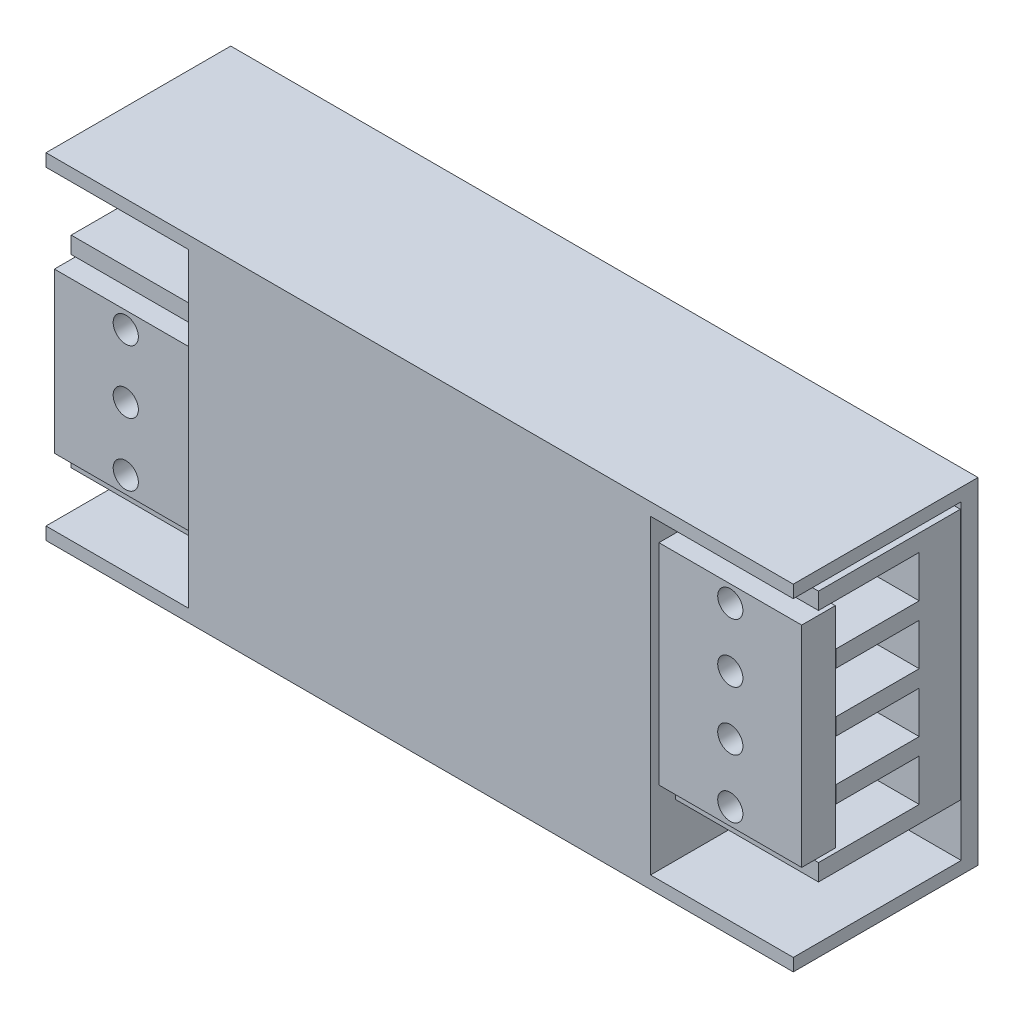
SolidWorks part; units mm, degrees
ref_plane "Front Plane" through (0, 0, 0) normal (0, 0, 1) x (1, 0, 0)
ref_plane "Top Plane" through (0, 0, 0) normal (0, 1, 0) x (1, 0, 0)
ref_plane "Right Plane" through (0, 0, 0) normal (1, 0, 0) x (0, 0, -1)
sketch "Sketch1" plane through (0, 0, 0) normal (0, 0, 1) x (1, 0, 0)
  line L1 (-44.5, 20) -> (44.5, 20)
  line L2 (-44.5, 20) -> (-44.5, -20)
  line L3 (-44.5, -20) -> (44.5, -20)
  line L4 (44.5, 20) -> (44.5, -20)
  line L5 (-44.5, 20) -> (44.5, -20) construction
  line L6 (-44.5, -20) -> (44.5, 20) construction
  point P0 (0, 0)
  dimension "D1" = 89
  dimension "D2" = 40
extrude "Boss-Extrude1" add sketch "Sketch1" along normal blind 22
sketch "Sketch2" plane through (0, 0, 22) normal (0, 0, 1) x (1, 0, 0)
  line L0 (44.5, 18.5) -> (-44.5, 18.5)
  line L1 (-44.5, -18.5) -> (44.5, -18.5)
  line L2 (-27.5, 18.5) -> (-27.5, -18.5)
  line L3 (27.5, 18.5) -> (27.5, -18.5)
  line L4 (44.5, -20) -> (44.5, 20)
  line L5 (44.5, 20) -> (-44.5, 20)
  line L6 (-44.5, 20) -> (-44.5, -20)
  line L7 (-44.5, -20) -> (44.5, -20)
  line L8 (44.5, -20) -> (44.5, 20)
  line L9 (44.5, 20) -> (-44.5, 20)
  line L10 (-44.5, 20) -> (-44.5, -20)
  line L11 (-44.5, -20) -> (44.5, -20)
  line M7 (44.5, -20) -> (44.5, 20)
  line M9 (-44.5, 20) -> (-44.5, -20)
  dimension "D3" = 17
  dimension "D4" = 17
  dimension "D1" = 0
  dimension "D2" = 1.5
extrude "Cut-Extrude1" cut sketch "Sketch2" against normal blind 20 contours L2 L0 L1 M9 | L0 L3 L1 M7
sketch "Sketch3" plane through (0, 0, 2) normal (0, 0, 1) x (1, 0, 0)
  line L0 (-44.5, 18.5) -> (-44.5, -18.5) construction
  line L1 (-44.5, 8) -> (-27.5, 8)
  line L2 (-44.5, 8) -> (-44.5, -12)
  line L3 (-44.5, -12) -> (-27.5, -12)
  line L4 (-27.5, 8) -> (-27.5, -12)
  line L5 (-27.5, 18.5) -> (-27.5, -18.5) construction
  line L6 (44.5, 20) -> (-44.5, 20) construction
  line L8 (-27.5, 1) -> (-44.5, 1)
  line L9 (-27.5, 1) -> (-27.5, 3)
  line L10 (-27.5, 3) -> (-44.5, 3)
  line L11 (-44.5, 1) -> (-44.5, 3)
  line L12 (-44.5, -5) -> (-27.5, -5)
  line L13 (-44.5, -5) -> (-44.5, -7)
  line L14 (-44.5, -7) -> (-27.5, -7)
  line L15 (-27.5, -5) -> (-27.5, -7)
  line L16 (-44.5, 8) -> (-27.5, 8)
  line L17 (-44.5, 8) -> (-44.5, 10)
  line L18 (-44.5, 10) -> (-27.5, 10)
  line L19 (-27.5, 8) -> (-27.5, 10)
  line L20 (-44.5, -12) -> (-27.5, -12)
  line L21 (-44.5, -12) -> (-44.5, -14)
  line L22 (-44.5, -14) -> (-27.5, -14)
  line L23 (-27.5, -12) -> (-27.5, -14)
  line M7 (-27.5, -18.5) -> (-27.5, 18.5)
  line M9 (-44.5, 18.5) -> (-44.5, -18.5)
  dimension "D1" = 20
  dimension "D2" = 12
  dimension "D3" = 2
  dimension "D4" = 2
  dimension "D5" = 5
  dimension "D6" = 5
  dimension "D7" = 2
  dimension "D8" = 2
extrude "Boss-Extrude2" add sketch "Sketch3" along normal blind 17 contours L18 L1 M9 M7 | L4 L10 L2 L8 | L14 L4 L12 M9 | L22 L3 M9 M7
sketch "Sketch4" plane through (0, 0, 19) normal (0, 0, 1) x (1, 0, 0)
  line L4 (-44.5, 7.5) -> (-44.5, -11.5)
  line L7 (-44.5, 8) -> (-27.5, 8) construction
  line L8 (-44.5, -7) -> (-27.5, -7) construction
  line L15 (-44.5, 10) -> (-44.5, 8) construction
  line L17 (-44.5, 10) -> (-27.5, 10) construction
  line L19 (-27.5, 7.5) -> (-27.5, -11.5)
  line L21 (-44.5, -11.5) -> (-27.5, -11.5)
  line L22 (-44.5, 7.5) -> (-27.5, 7.5)
  line L23 (44.5, 20) -> (-44.5, 20) construction
  circle A0 centre (-36, 5.5) radius 1.5
  circle A1 centre (-36, -2) radius 1.5
  circle A2 centre (-36, -9.5) radius 1.5
  dimension "D1" = 2.5
  dimension "D2" = 3
  dimension "D4" = 12
  dimension "D6" = 17
  dimension "D3" = 8.5
  dimension "D5" = 19
  dimension "D7" = 2.5
  dimension "D8" = 12.5
extrude "Boss-Extrude10" add sketch "Sketch4" against normal blind 2 and the other way blind 2
sketch "Sketch5" plane through (0, 0, 2) normal (0, 0, 1) x (1, 0, 0)
  line L0 (27.5, 18.5) -> (27.5, -18.5) construction
  line L1 (27.5, 17.778) -> (44.5, 17.778)
  line L2 (27.5, 17.778) -> (27.5, -12.222)
  line L3 (27.5, -12.222) -> (44.5, -12.222)
  line L4 (44.5, 17.778) -> (44.5, -12.222)
  line L5 (44.5, -18.5) -> (44.5, 18.5) construction
  line L6 (27.5, 15.778) -> (44.5, 15.778)
  line L7 (27.5, 10.778) -> (44.5, 10.778)
  line L8 (27.5, 10.778) -> (27.5, 8.778)
  line L9 (27.5, 8.778) -> (44.5, 8.778)
  line L10 (44.5, 10.778) -> (44.5, 8.778)
  line L11 (27.5, -10.222) -> (44.5, -10.222)
  line L12 (27.5, 3.778) -> (44.5, 3.778)
  line L13 (27.5, 3.778) -> (27.5, 1.778)
  line L14 (27.5, 1.778) -> (44.5, 1.778)
  line L15 (44.5, 3.778) -> (44.5, 1.778)
  line L16 (27.5, -3.222) -> (44.5, -3.222)
  line L17 (27.5, -3.222) -> (27.5, -5.222)
  line L18 (27.5, -5.222) -> (44.5, -5.222)
  line L19 (44.5, -3.222) -> (44.5, -5.222)
  line L21 (44.5, 18.5) -> (27.5, 18.5) construction
  line M14 (27.5, 18.5) -> (27.5, -18.5)
  line M16 (44.5, -18.5) -> (44.5, 18.5)
  dimension "D1" = 30
  dimension "D2" = 0.722
  dimension "D3" = 2.722
  dimension "D4" = 7.722
  dimension "D5" = 9.722
  dimension "D6" = 14.722
  dimension "D7" = 21.722
  dimension "D10" = 28.722
extrude "Boss-Extrude11" add sketch "Sketch5" along normal blind 17 contours L6 L4 L1 M14 | L9 L4 L7 M14 | L14 L12 M14 M16 | L18 L16 M14 M16 | L11 L3 M14 M16
sketch "Sketch6" plane through (0, 0, 19) normal (0, 0, 1) x (1, 0, 0)
  line L0 (27.5, 18.5) -> (27.5, -18.5) construction
  line L1 (27.5, 15.778) -> (44.5, 15.778) construction
  line L3 (27.5, 15.278) -> (27.5, -9.722)
  line L6 (44.5, 15.278) -> (44.5, -9.722)
  line L8 (27.5, -5.222) -> (44.5, -5.222) construction
  line L9 (27.5, 1.778) -> (44.5, 1.778) construction
  line L10 (27.5, 8.778) -> (44.5, 8.778) construction
  line L11 (27.5, 15.278) -> (44.5, 15.278)
  line L12 (44.5, -9.722) -> (27.5, -9.722)
  line L13 (-44.5, -20) -> (44.5, -20) construction
  circle A0 centre (36, 13.278) radius 1.5
  circle A1 centre (36, 6.278) radius 1.5
  circle A2 centre (36, -0.722) radius 1.5
  circle A3 centre (36, -7.722) radius 1.5
  point P18 (36, 1.778)
  dimension "D1" = 3
  dimension "D2" = 2.5
  dimension "D3" = 2.5
  dimension "D4" = 2.5
  dimension "D5" = 25
  dimension "D6" = 8.5
  dimension "D7" = 8.5
  dimension "D8" = 8.5
  dimension "D9" = 8.5
  dimension "D10" = 0.5
  dimension "D12" = 2
  dimension "D13" = 10.278
extrude "Boss-Extrude13" add sketch "Sketch6" against normal blind 2 and the other way blind 2
sketch "Sketch7" plane through (-44.5, 0, 0) normal (-1, 0, 0) x (0, 0, 1)
  line L0 (19, 8) -> (2, 8) construction
  line L1 (2, 10) -> (2.1, 10)
  line L2 (2, 10) -> (2, 8)
  line L3 (2, 8) -> (2.1, 8)
  line L4 (2.1, 10) -> (2.1, 8)
  line L5 (17, 1) -> (2, 1) construction
  line L6 (2, 3) -> (2.1, 3)
  line L7 (2, 3) -> (2, 1)
  line L8 (2, 1) -> (2.1, 1)
  line L9 (2.1, 3) -> (2.1, 1)
  line L10 (17, -7) -> (2, -7) construction
  line L11 (2, -5) -> (2.1, -5)
  line L12 (2, -5) -> (2, -7)
  line L13 (2, -7) -> (2.1, -7)
  line L14 (2.1, -5) -> (2.1, -7)
  line L15 (19, -14) -> (2, -14) construction
  line L16 (2, -12) -> (2.1, -12)
  line L17 (2, -12) -> (2, -14)
  line L18 (2, -14) -> (2.1, -14)
  line L19 (2.1, -12) -> (2.1, -14)
  line L21 (17, -5) -> (16.9, -5)
  line L22 (17, -5) -> (17, -7)
  line L23 (17, -7) -> (16.9, -7)
  line L24 (16.9, -5) -> (16.9, -7)
  line L25 (17, 3) -> (16.9, 3)
  line L26 (17, 3) -> (17, 1)
  line L27 (17, 1) -> (16.9, 1)
  line L28 (16.9, 3) -> (16.9, 1)
  point P21 (2, -6)
  dimension "D1" = 0.1
  dimension "D2" = 0.1
  dimension "D3" = 0.1
  dimension "D4" = 0.1
  dimension "D5" = 0.1
  dimension "D6" = 0.1
extrude "Cut-Extrude2" cut sketch "Sketch7" against normal up to surface (17 mm away) up to face at (-27.5, -2, 9.5)
sketch "Sketch8" plane through (44.5, 0, 0) normal (1, 0, 0) x (0, 0, -1)
  line L5 (-17, -3.222) -> (-2, -3.222) construction
  line L6 (-2, -5.222) -> (-2.1, -5.222)
  line L7 (-2, -5.222) -> (-2, -3.222)
  line L8 (-2, -3.222) -> (-2.1, -3.222)
  line L9 (-2.1, -5.222) -> (-2.1, -3.222)
  line L10 (-17, -5.222) -> (-2, -5.222) construction
  line L11 (-17, -3.222) -> (-16.9, -3.222)
  line L12 (-17, -3.222) -> (-17, -5.222)
  line L13 (-17, -5.222) -> (-16.9, -5.222)
  line L14 (-16.9, -3.222) -> (-16.9, -5.222)
  line L15 (-17, 1.778) -> (-2, 1.778) construction
  line L16 (-17, 3.778) -> (-16.9, 3.778)
  line L17 (-17, 3.778) -> (-17, 1.778)
  line L18 (-17, 1.778) -> (-16.9, 1.778)
  line L19 (-16.9, 3.778) -> (-16.9, 1.778)
  line L20 (-17, 8.778) -> (-2, 8.778) construction
  line L21 (-17, 10.778) -> (-16.9, 10.778)
  line L22 (-17, 10.778) -> (-17, 8.778)
  line L23 (-17, 8.778) -> (-16.9, 8.778)
  line L24 (-16.9, 10.778) -> (-16.9, 8.778)
  line L25 (-19, 17.778) -> (-2, 17.778) construction
  line L30 (-17, 3.778) -> (-2, 3.778) construction
  line L31 (-2, 15.778) -> (-2.1, 15.778)
  line L32 (-2, 15.778) -> (-2, 17.778)
  line L33 (-2, 17.778) -> (-2.1, 17.778)
  line L34 (-2.1, 15.778) -> (-2.1, 17.778)
  line L35 (-2, 10.778) -> (-2.1, 10.778)
  line L36 (-2, 10.778) -> (-2, 8.778)
  line L37 (-2, 8.778) -> (-2.1, 8.778)
  line L38 (-2.1, 10.778) -> (-2.1, 8.778)
  line L39 (-2, 1.778) -> (-2.1, 1.778)
  line L40 (-2, 1.778) -> (-2, 3.778)
  line L41 (-2, 3.778) -> (-2.1, 3.778)
  line L42 (-2.1, 1.778) -> (-2.1, 3.778)
  line L43 (-19, -12.222) -> (-2, -12.222) construction
  line L48 (-2, -10.222) -> (-2.1, -10.222)
  line L49 (-2, -10.222) -> (-2, -12.222)
  line L50 (-2, -12.222) -> (-2.1, -12.222)
  line L51 (-2.1, -10.222) -> (-2.1, -12.222)
  point P59 (-17, 2.778)
  point P60 (-17, -4.222)
  dimension "D1" = 0.1
  dimension "D2" = 0.1
  dimension "D3" = 0.1
  dimension "D4" = 0.1
  dimension "D5" = 0.1
  dimension "D6" = 0.1
  dimension "D7" = 0.1
  dimension "D8" = 0.1
extrude "Cut-Extrude11" cut sketch "Sketch8" against normal up to surface (17 mm away) up to face at (27.5, -0.722, 9.5)
sketch "Sketch10" plane through (0, 0, 2) normal (0, 0, 1) x (1, 0, 0)
  line L0 (-27.5, 8) -> (-44.5, 8) construction
  line L1 (-27.5, 8) -> (-44.5, 8)
  line L2 (-27.5, 3) -> (-44.5, 3) construction
  line L3 (-27.5, 3) -> (-44.5, 3)
  line L4 (-27.5, 1) -> (-44.5, 1) construction
  line L5 (-27.5, 1) -> (-44.5, 1)
  line L6 (-27.5, -5) -> (-44.5, -5) construction
  line L7 (-27.5, -5) -> (-44.5, -5)
  line L8 (-27.5, -7) -> (-44.5, -7) construction
  line L9 (-27.5, -7) -> (-44.5, -7)
  line L10 (-27.5, -12) -> (-44.5, -12) construction
  line L11 (-27.5, -12) -> (-44.5, -12)
  line L12 (-44.5, -12) -> (-44.5, -7)
  line L13 (-44.5, -5) -> (-44.5, 1)
  line L14 (-44.5, 3) -> (-44.5, 8)
  line L15 (-27.5, 8) -> (-27.5, 3)
  line L16 (-27.5, 1) -> (-27.5, -5)
  line L17 (-27.5, -7) -> (-27.5, -12)
extrude "Boss-Extrude14" add sketch "Sketch10" along normal blind 5
sketch "Sketch11" plane through (-44.5, 0, 0) normal (-1, 0, 0) x (0, 0, 1)
  line L0 (2.1, 8) -> (2.1, -12)
  line L1 (2.1, -12) -> (2, -12)
  line L2 (2, -12) -> (2, 8)
  line L3 (2.1, 8) -> (2, 8) construction
  line L4 (2.1, 8) -> (2, 8)
extrude "Cut-Extrude12" cut sketch "Sketch11" against normal up to surface (17 mm away) up to face at (-27.5, 2, 2.05)
sketch "Sketch12" plane through (0, 0, 2) normal (0, 0, 1) x (1, 0, 0)
  line L0 (27.5, -10.222) -> (44.5, -10.222) construction
  line L1 (27.5, -10.222) -> (44.5, -10.222)
  line L2 (27.5, -5.222) -> (44.5, -5.222) construction
  line L3 (27.5, -5.222) -> (44.5, -5.222)
  line L4 (27.5, -3.222) -> (44.5, -3.222) construction
  line L5 (27.5, -3.222) -> (44.5, -3.222)
  line L6 (27.5, 1.778) -> (44.5, 1.778) construction
  line L7 (27.5, 1.778) -> (44.5, 1.778)
  line L8 (27.5, 3.778) -> (44.5, 3.778) construction
  line L9 (27.5, 3.778) -> (44.5, 3.778)
  line L10 (27.5, 8.778) -> (44.5, 8.778) construction
  line L11 (27.5, 8.778) -> (44.5, 8.778)
  line L12 (27.5, 10.778) -> (44.5, 10.778) construction
  line L13 (27.5, 10.778) -> (44.5, 10.778)
  line L14 (27.5, 15.778) -> (44.5, 15.778) construction
  line L15 (27.5, 15.778) -> (44.5, 15.778)
  line L16 (44.5, 15.778) -> (44.5, -10.222)
  line L17 (27.5, 15.778) -> (27.5, -10.222)
  line M2 (27.5, 18.5) -> (27.5, -18.5)
  line M4 (44.5, -18.5) -> (44.5, 18.5)
extrude "Boss-Extrude15" add sketch "Sketch12" along normal blind 5 contours L15 L13 M2 M4 | L11 L9 M2 M4 | L7 L5 M2 M4 | L3 L1 M2 M4
sketch "Sketch13" plane through (44.5, 0, 0) normal (1, 0, 0) x (0, 0, -1)
  line L0 (-2.1, 15.778) -> (-2.1, -10.222)
  line L1 (-2.1, -10.222) -> (-2, -10.222)
  line L2 (-2, -10.222) -> (-2, 15.778)
  line L3 (-2, 15.778) -> (-2.1, 15.778)
extrude "Cut-Extrude13" cut sketch "Sketch13" against normal up to surface (17 mm away) up to face at (27.5, 9.778, 2.05)
